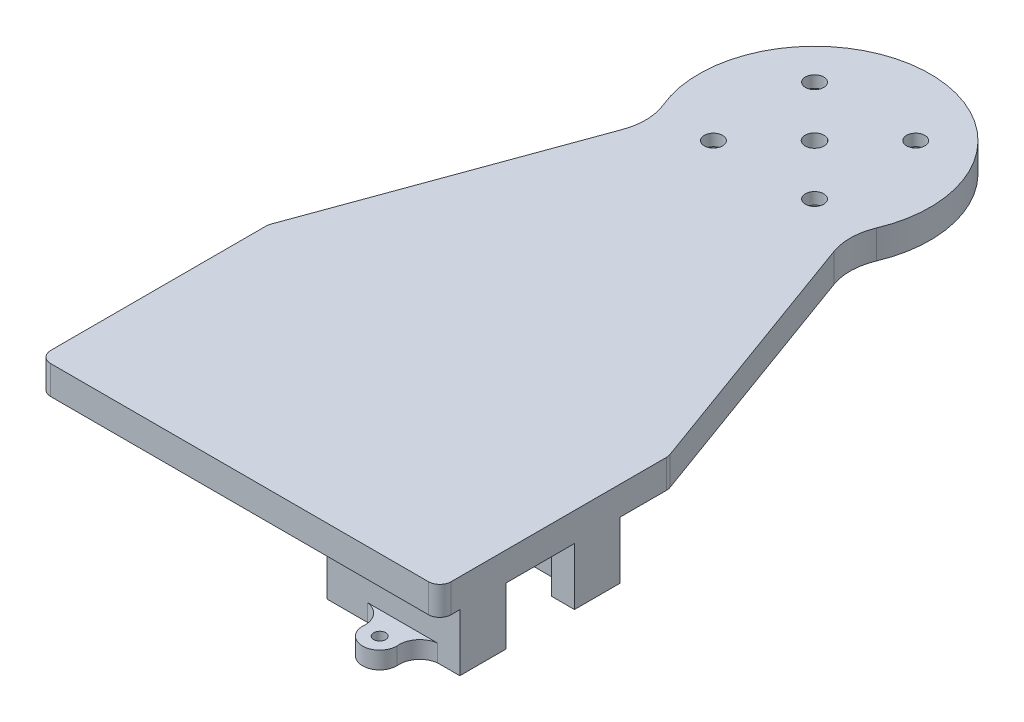
SolidWorks part; units mm, degrees
material "ABS"
ref_plane "Front Plane" through (0, 0, 0) normal (0, 0, 1) x (1, 0, 0)
ref_plane "Top Plane" through (0, 0, 0) normal (0, 1, 0) x (1, 0, 0)
ref_plane "Right Plane" through (0, 0, 0) normal (1, 0, 0) x (0, 0, -1)
sketch "Sketch9" plane through (0, 0, 0) normal (0, 1, 0) x (1, 0, 0)
  line L0 (-35, -85.9862) -> (35, -85.9862)
  line L1 (35, -85.9862) -> (24.5726, -57.3372)
  line L2 (0, -70.6481) -> (0, -106.5937) construction
  line L3 (24.5726, -57.3372) -> (16.969, -36.4465)
  line L4 (-24.5726, -57.3372) -> (-16.969, -36.4465)
  line L5 (-35, -85.9862) -> (-24.5726, -57.3372)
  circle A0 centre (0, -25.4862) radius 20.2009
  point P11 (0, -85.9862)
  dimension "D1" = 35
  dimension "D2" = 60.5
  dimension "D3" = 70
extrude "Boss-Extrude4" add sketch "Sketch9" along normal blind 5
sketch "Sketch10" plane through (0, 5, 0) normal (0, 1, 0) x (1, 0, 0)
  line L0 (-16.969, -36.4465) -> (16.969, -36.4465)
sketch "Sketch11" plane through (0, 0, 85.9862) normal (0, 0, 1) x (1, 0, 0)
  line L0 (0, 5) -> (0, 0) construction
  line L1 (-35, 5) -> (35, 5)
  line L2 (-35, 5) -> (-35, 0)
  line L3 (-35, 0) -> (35, 0)
  line L4 (35, 5) -> (35, 0)
  line L5 (-35, 5) -> (35, 0) construction
  line L6 (-35, 0) -> (35, 5) construction
  line L7 (-35, 5) -> (35, 5) construction
  point P0 (0, 2.5)
  dimension "D1" = 70
  dimension "D2" = 5
extrude "Boss-Extrude5" add sketch "Sketch11" along normal blind 40
ref_plane "Plane7" through (0, 0, 94.49) normal (0, 0, 1) x (1, 0, 0)
ref_plane "Plane10" through (0, 5000, 0) normal (0, 1, 0) x (1, 0, 0)
sketch "Sketch19" plane through (0, 0, 0) normal (0, 1, 0) x (1, 0, 0)
  line L1 (0, -2.75) -> (0, 2.75) construction
  line L22 (31, -117.4862) -> (-31, -117.4862)
  line L23 (31, -117.4862) -> (31, -122.4862)
  line L24 (31, -122.4862) -> (-31, -122.4862)
  line L25 (-31, -117.4862) -> (-31, -122.4862)
  line L26 (31, -117.4862) -> (-31, -122.4862) construction
  line L27 (31, -122.4862) -> (-31, -117.4862) construction
  point P0 (0, -119.9862)
  dimension "D1" = 5
  dimension "D2" = 62
fillet "Fillet1" radius 10 1 edges at (-16.969, 2.5, 36.4465)
fillet "Fillet2" radius 10 1 edges at (16.969, 2.5, 36.4465)
sketch "Sketch20" plane through (0, 0, 0) normal (0, -1, 0) x (-1, 0, 0)
  line L0 (0, 2.75) -> (0, -2.75) construction
  line L1 (31, -94.49) -> (-31, -94.49)
  line L2 (31, -94.49) -> (31, -99.49)
  line L3 (31, -99.49) -> (-31, -99.49)
  line L4 (-31, -94.49) -> (-31, -99.49)
  line L5 (31, -94.49) -> (-31, -99.49) construction
  line L6 (31, -99.49) -> (-31, -94.49) construction
  line L8 (-2.75, -94.49) -> (2.75, -94.49) construction
  point P0 (0, -96.99)
  dimension "D1" = 62
  dimension "D2" = 5
sketch "Sketch21" plane through (0, 0, 0) normal (0, -1, 0) x (-1, 0, 0)
  circle A0 centre (8.8388, -16.6474) radius 1.6
  dimension "D1" = 3.2
  dimension "D2" = 12.5
extrude "Cut-Extrude1" cut sketch "Sketch21" against normal through all
pattern_circular "CirPattern1" count 4 over 360 about axis through (0, 0, 25.4862) along (0, 1, 0) of "Cut-Extrude1"
sketch "Sketch22" plane through (0, 0, 0) normal (0, -1, 0) x (-1, 0, 0)
  circle A0 centre (8.8388, -16.6474) radius 2.86
extrude "Cut-Extrude2" cut sketch "Sketch22" against normal blind 2.95
pattern_circular "CirPattern2" count 4 over 360 about axis through (0, 0, 25.4862) along (0, 1, 0) of "Cut-Extrude2"
fillet "Fillet4" radius 2 4 edges at (-35, 2.5, 125.9862) (35, 2.5, 125.9862) (35, 2.5, 85.9862) (-35, 2.5, 85.9862)
sketch "Sketch24" plane through (0, 5, 0) normal (0, 1, 0) x (1, 0, 0)
  line L1 (3.4443, -27.5447) -> (3.5049, -23.5325)
  line L2 (3.5049, -23.5325) -> (0.0605, -21.4741)
  line L3 (0.0605, -21.4741) -> (-3.4443, -23.4277)
  line L4 (-3.4443, -23.4277) -> (-3.5049, -27.4398)
  line L5 (-3.5049, -27.4398) -> (-0.0605, -29.4983)
  line L6 (-0.0605, -29.4983) -> (3.4443, -27.5447)
  circle A0 centre (0, -25.4862) radius 3.475 construction
  dimension "D1" = 6.95
ref_plane "Plane11" through (-35, 0, 0) normal (1, 0, 0) x (0, 0, -1)
sketch "Sketch25" plane through (-35, 0, -0.5055) normal (1, 0, 0) x (0, 0, -1)
  line L0 (-124.4916, 0) -> (-86.8443, 0) construction
  line L1 (-118.49, -10) -> (-99.49, -10)
  line L2 (-118.49, -10) -> (-118.49, 0)
  line L3 (-118.49, 0) -> (-99.49, 0)
  line L4 (-99.49, -10) -> (-99.49, 0)
  line L5 (-118.49, -10) -> (-99.49, 0) construction
  line L6 (-118.49, 0) -> (-99.49, -10) construction
  point P0 (-108.99, -5)
  dimension "D1" = 19
  dimension "D2" = 10
extrude "Boss-Extrude6" add sketch "Sketch25" along normal blind 4
sketch "Sketch26" plane through (-31, 0, -0.5055) normal (1, 0, 0) x (0, 0, -1)
  line L1 (-103.44, -16) -> (-114.54, -16)
  line L2 (-103.44, -16) -> (-103.44, -4)
  line L3 (-103.44, -4) -> (-114.54, -4)
  line L4 (-114.54, -16) -> (-114.54, -4)
  line L5 (-103.44, -16) -> (-114.54, -4) construction
  line L6 (-103.44, -4) -> (-114.54, -16) construction
  line L7 (-118.49, -10) -> (-99.49, -10) construction
  point P0 (-108.99, -10)
  dimension "D1" = 11.1
  dimension "D2" = 12
extrude "Cut-Extrude4" cut sketch "Sketch26" along normal blind 9.5 and the other way blind 5.5
sketch "Sketch31" plane through (-31, 0, 0) normal (1, 0, 0) x (0, 0, -1)
  line L0 (-99.4845, -4) -> (-102.9345, -4)
  line L1 (-102.9345, -4) -> (-102.9345, -4.5)
  line L2 (-102.9345, -4) -> (-102.9345, -10) construction
  line L3 (-102.9345, -4.5) -> (-98.9845, -4.5)
  line L4 (-98.9845, -10) -> (-98.9845, 0) construction
  line L5 (-98.9845, -4.5) -> (-98.9845, 0)
  line L6 (-98.9845, 0) -> (-117.9845, 0)
  line L7 (-117.9845, 0) -> (-117.9845, -10) construction
  line L8 (-117.9845, 0) -> (-117.9845, -4.5)
  line L9 (-117.9845, -4.5) -> (-114.0345, -4.5)
  line L10 (-114.0345, -10) -> (-114.0345, -4) construction
  line L11 (-114.0345, -4.5) -> (-114.0345, -4)
  line L12 (-114.0345, -4) -> (-117.4845, -4)
  line L13 (-117.4845, -4) -> (-117.4845, -2.4)
  line L14 (-117.4845, -2.4) -> (-99.4845, -2.4)
  line L15 (-99.4845, -2.4) -> (-99.4845, -4)
  line L16 (38.5, 0) -> (-38.5, 0) construction
  dimension "D1" = 0.5
  dimension "D2" = 0.5
  dimension "D3" = 0.5
  dimension "D4" = 0.5
  dimension "D5" = 0
  dimension "D6" = 1.6
extrude "Boss-Extrude9" add sketch "Sketch31" along normal blind 1.5
ref_plane "Plane12" through (35, 0, 0) normal (1, 0, 0) x (0, 0, -1)
sketch "Sketch32" plane through (0, 0, 0) normal (0, -1, 0) x (1, 0, 0)
  line L0 (31, 99.49) -> (31, 102.4473)
  line L1 (31, 102.4473) -> (35, 102.4473)
  line L2 (35, 123.9862) -> (35, 86.3388) construction
  line L3 (35, 102.4473) -> (35, 94.49)
  line L4 (35, 94.49) -> (20.0797, 94.49)
  line L7 (31, 117.4862) -> (31, 114.3753)
  line L8 (31, 114.3753) -> (35, 114.3753)
  line L9 (35, 114.3753) -> (35, 122.4862)
  line L10 (35, 122.4862) -> (20.0797, 122.4862)
  line L13 (20.0797, 94.49) -> (11.7508, 94.49)
  line L14 (11.7508, 94.49) -> (11.7508, 99.49)
  line L15 (11.7508, 99.49) -> (31, 99.49)
  line L16 (20.0797, 122.4862) -> (11.7508, 122.4862)
  line L17 (11.7508, 122.4862) -> (11.7508, 117.4862)
  line L18 (11.7508, 117.4862) -> (31, 117.4862)
extrude "Boss-Extrude10" add sketch "Sketch32" along normal blind 10
sketch "Sketch35" plane through (0, 0, 0) normal (0, -1, 0) x (-1, 0, 0)
  line L0 (-31, -117.4862) -> (-31, -99.49)
  line L1 (-31, -99.49) -> (-20.0797, -99.49)
  line L2 (-20.0797, -99.49) -> (-20.0797, -117.4862)
  line L3 (-20.0797, -117.4862) -> (-31, -117.4862)
extrude "Boss-Extrude11" add sketch "Sketch35" along normal blind 2.4
sketch "Sketch36" plane through (0, -10, 0) normal (0, -1, 0) x (1, 0, 0)
  line L0 (33.4938, 108.49) -> (-47.7872, 108.49) construction
  line L1 (-31, 99.49) -> (31, 99.49) construction
  line L2 (35, 114.3753) -> (35, 122.4862) construction
  line L3 (31.1093, 94.4938) -> (18.846, 94.4938)
  line L4 (35, 122.4862) -> (11.7508, 122.4862) construction
  line L5 (31.1093, 122.4862) -> (18.846, 122.4862)
  circle A0 centre (25, 126.49) radius 3
  arc A1 (28, 126.49) -> (31.1093, 122.4862) centre (31.5738, 126.0561) ccw
  arc A2 (22, 126.49) -> (18.846, 122.4862) centre (18.4211, 126.0651) cw
  arc A3 (28, 90.49) -> (31.1093, 94.4938) centre (31.5738, 90.9239) cw
  arc A4 (22, 90.49) -> (18.846, 94.4938) centre (18.4211, 90.9149) ccw
  circle A5 centre (25, 90.49) radius 3
  line M5 (35, 122.4862) -> (11.7508, 122.4862)
  dimension "D3" = 18
  dimension "D4" = 3.604
  dimension "D5" = 3.6
  dimension "D1" = 9
  dimension "D2" = 10
extrude "Boss-Extrude12" add sketch "Sketch36" against normal blind 3 contours A0 A2 A1 | A0 A2 A1 M5 | A5 A4 A3 | A4 A5 A3 L3
sketch "Sketch37" plane through (0, -10, 0) normal (0, -1, 0) x (-1, 0, 0)
  line L0 (-32.322, -108.49) -> (-4.917, -108.49) construction
  line L2 (31, -99.49) -> (-31, -99.49) construction
  circle A0 centre (-25, -126.49) radius 1.05
  circle A1 centre (-25, -90.49) radius 1.05
  dimension "D2" = 9
extrude "Cut-Extrude6" cut sketch "Sketch37" against normal blind 3
sketch "Sketch39" plane through (0, 0, 0) normal (0, -1, 0) x (-1, 0, 0)
  circle A0 centre (0, -25.4862) radius 1.65
extrude "Cut-Extrude7" cut sketch "Sketch39" against normal through all
sketch "Sketch40" plane through (0, -10, 0) normal (0, -1, 0) x (-1, 0, 0)
  line L0 (31, -117.9845) -> (35, -117.9845) construction
  line L1 (31, -98.9845) -> (35, -98.9845)
  line L2 (31, -98.9845) -> (31, -117.9845)
  line L3 (31, -117.9845) -> (35, -117.9845)
  line L4 (35, -98.9845) -> (35, -117.9845)
extrude "Cut-Extrude8" cut sketch "Sketch40" against normal blind 5.5
